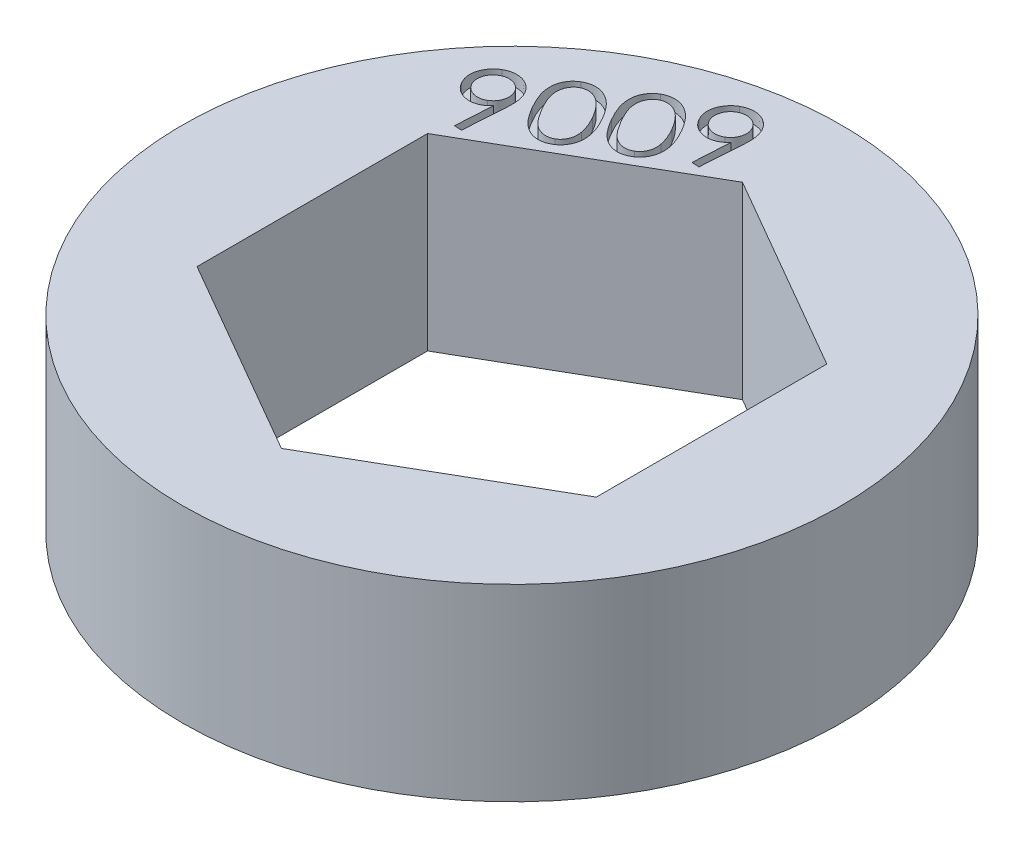
SolidWorks part; units mm, degrees
material "ABS"
ref_plane "Front Plane" through (0, 0, 0) normal (0, 0, 1) x (1, 0, 0)
ref_plane "Top Plane" through (0, 0, 0) normal (0, 1, 0) x (1, 0, 0)
ref_plane "Right Plane" through (0, 0, 0) normal (1, 0, 0) x (0, 0, -1)
sketch "Sketch1" plane through (0, 0, 0) normal (0, 1, 0) x (1, 0, 0)
  line L1 (0, 7.7723) -> (-6.731, 3.8861)
  line L2 (-6.731, 3.8861) -> (-6.731, -3.8861)
  line L3 (-6.731, -3.8861) -> (0, -7.7723)
  line L4 (0, -7.7723) -> (6.731, -3.8861)
  line L5 (6.731, -3.8861) -> (6.731, 3.8861)
  line L6 (6.731, 3.8861) -> (0, 7.7723)
  circle A0 centre (0, 0) radius 11.1125
  circle A1 centre (0, 0) radius 6.731 construction
  dimension "D1" = 22.225
  dimension "D2" = 13.462
extrude "Boss-Extrude1" add sketch "Sketch1" along normal blind 6.35
sketch "Sketch2" plane through (0, 6.35, 0) normal (0, 1, 0) x (1, 0, 0)
  line L0 (-6.8756, 4.2719) -> (-0.5001, 7.9528) construction
  line L1 (0, 7.7723) -> (-6.731, 3.8861) construction
  text T0 "9009" font "Century Gothic" height 2.54
  dimension "D1" = 0.4064
extrude "Cut-Extrude1" cut sketch "Sketch2" against normal blind 0.4
